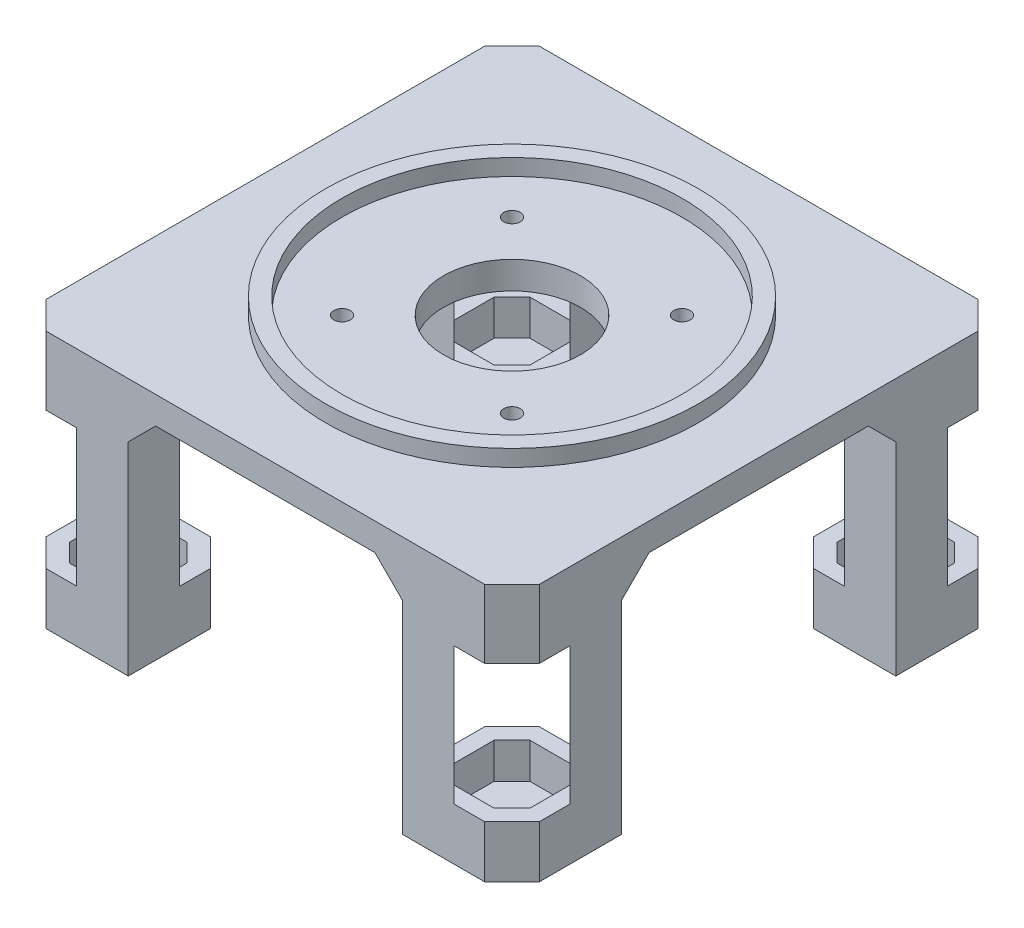
SolidWorks part; units mm, degrees
material "聚脂树脂"
ref_plane "前视基准面" through (0, 0, 0) normal (0, 0, 1) x (1, 0, 0)
ref_plane "上视基准面" through (0, 0, 0) normal (0, 1, 0) x (1, 0, 0)
ref_plane "右视基准面" through (0, 0, 0) normal (1, 0, 0) x (0, 0, -1)
other "Configuration Table"
sketch "草图1" plane through (0, 0, 0) normal (0, 1, 0) x (1, 0, 0)
  line L0 (0, 0) -> (0, 27.7353) construction
  line L1 (-45, -45) -> (45, -45)
  line L2 (-45, -45) -> (-45, 45)
  line L3 (-45, 45) -> (45, 45)
  line L4 (45, -45) -> (45, 45)
  line L5 (-45, -45) -> (45, 45) construction
  line L6 (-45, 45) -> (45, -45) construction
  circle A0 centre (0, 0) radius 12.5
  circle A1 centre (15.5, 15.5) radius 1.5
  circle A2 centre (-15.5, -15.5) radius 1.5
  circle A3 centre (15.5, -15.5) radius 1.5
  circle A4 centre (-15.5, 15.5) radius 1.5
  circle A5 centre (0, 0) radius 34 construction
  point P0 (0, 0)
  dimension "D1" = 25
  dimension "D2" = 3
  dimension "D3" = 31
  dimension "D4" = 31
  dimension "D6" = 68
  dimension "D5" = 90
extrude "凸台-拉伸1" add sketch "草图1" along normal blind 5
chamfer "倒角1" distance 5 angle 45 4 edges at (-45, 2.5, -45) (-45, 2.5, 45) (45, 2.5, -45) (45, 2.5, 45)
sketch "草图2" plane through (0, 5, 0) normal (0, 1, 0) x (1, 0, 0)
  circle A0 centre (0, 0) radius 31
  circle A1 centre (0, 0) radius 34
  dimension "D1" = 62
  dimension "D2" = 68
extrude "凸台-拉伸2" add sketch "草图2" along normal blind 3
sketch "草图3" plane through (0, 0, 0) normal (0, -1, 0) x (1, 0, 0)
  line L0 (0, 0) -> (0, 54.7666) construction
  line L1 (0, 0) -> (54.8608, 0) construction
  line L2 (25, 45) -> (40, 45)
  line L3 (-40, 45) -> (40, 45) construction
  line L4 (40, 45) -> (45, 40)
  line L5 (45, 40) -> (45, 25)
  line L6 (45, 40) -> (45, -40) construction
  line L7 (45, 25) -> (30, 25)
  line L8 (25, 45) -> (25, 30)
  line L9 (25, 30) -> (30, 25)
  line L10 (28, 31.2426) -> (31.2426, 28)
  line L11 (42, 28) -> (31.2426, 28)
  line L12 (42, 38.7574) -> (42, 28)
  line L13 (38.7574, 42) -> (42, 38.7574)
  line L14 (28, 42) -> (38.7574, 42)
  line L15 (28, 42) -> (28, 31.2426)
  line L16 (25, -45) -> (25, -30)
  line L17 (25, -45) -> (40, -45)
  line L18 (40, -45) -> (45, -40)
  line L19 (45, -40) -> (45, -25)
  line L20 (45, -25) -> (30, -25)
  line L21 (25, -30) -> (30, -25)
  line L22 (28, -42) -> (28, -31.2426)
  line L23 (28, -42) -> (38.7574, -42)
  line L24 (38.7574, -42) -> (42, -38.7574)
  line L25 (42, -38.7574) -> (42, -28)
  line L26 (42, -28) -> (31.2426, -28)
  line L27 (28, -31.2426) -> (31.2426, -28)
  line L28 (-25, -45) -> (-40, -45)
  line L29 (-40, -45) -> (-45, -40)
  line L30 (-45, -40) -> (-45, -25)
  line L31 (-45, -25) -> (-30, -25)
  line L32 (-25, -30) -> (-30, -25)
  line L33 (-25, -45) -> (-25, -30)
  line L34 (-28, -42) -> (-38.7574, -42)
  line L35 (-38.7574, -42) -> (-42, -38.7574)
  line L36 (-42, -38.7574) -> (-42, -28)
  line L37 (-42, -28) -> (-31.2426, -28)
  line L38 (-28, -31.2426) -> (-31.2426, -28)
  line L39 (-28, -42) -> (-28, -31.2426)
  line L40 (-25, 45) -> (-25, 30)
  line L41 (-25, 45) -> (-40, 45)
  line L42 (-40, 45) -> (-45, 40)
  line L43 (-45, 40) -> (-45, 25)
  line L44 (-45, 25) -> (-30, 25)
  line L45 (-25, 30) -> (-30, 25)
  line L46 (-28, 42) -> (-28, 31.2426)
  line L47 (-28, 42) -> (-38.7574, 42)
  line L48 (-38.7574, 42) -> (-42, 38.7574)
  line L49 (-42, 38.7574) -> (-42, 28)
  line L50 (-42, 28) -> (-31.2426, 28)
  line L51 (-28, 31.2426) -> (-31.2426, 28)
  circle A0 centre (0, 0) radius 30 construction
  dimension "D2" = 60
  dimension "D3" = 5
  dimension "D1" = 15
  dimension "D4" = 5
  dimension "D5" = 15
  dimension "D6" = 3
extrude "凸台-拉伸3" add sketch "草图3" along normal blind 42
chamfer "倒角2" distance 5 angle 45 8 edges at (37.5, 0, -25) (25, 0, 37.5) (37.5, 0, 25) (25, 0, -37.5) (-25, 0, 37.5) (-37.5, 0, 25) (-25, 0, -37.5) (-37.5, 0, -25)
sketch "草图4" plane through (-42.5, 0, 42.5) normal (-0.7071, 0, 0.7071) x (0.7071, 0, 0.7071)
  line L0 (0, 0) -> (0, -44.657) construction
  line L1 (-3.5355, 5) -> (3.5355, 5) construction
  line L2 (-7.5, -32.5) -> (7.5, -32.5)
  line L3 (-7.5, -32.5) -> (-7.5, -7.5)
  line L4 (-7.5, -7.5) -> (7.5, -7.5)
  line L5 (7.5, -32.5) -> (7.5, -7.5)
  line L6 (-7.5, -32.5) -> (7.5, -7.5) construction
  line L7 (-7.5, -7.5) -> (7.5, -32.5) construction
  point P3 (0, -20)
  dimension "D1" = 15
  dimension "D2" = 25
  dimension "D3" = 25
extrude "切除-拉伸1" cut sketch "草图4" against normal blind 157
pattern_circular "阵列(圆周)1" count 2 over 90 about axis through (0, 8, 0) along (0, -1, 0) of "切除-拉伸1"
sketch "草图5" plane through (0, -42, 0) normal (0, -1, 0) x (1, 0, 0)
  line L0 (-25, -45) -> (-25, -30) construction
  line L1 (-25, -30) -> (-30, -25) construction
  line L2 (-30, -25) -> (-45, -25) construction
  line L3 (-45, -25) -> (-45, -40) construction
  line L4 (-45, -40) -> (-40, -45) construction
  line L5 (-40, -45) -> (-25, -45) construction
  line L6 (40, -45) -> (45, -40) construction
  line L7 (45, -40) -> (45, -25) construction
  line L8 (45, -25) -> (30, -25) construction
  line L9 (30, -25) -> (25, -30) construction
  line L10 (25, -30) -> (25, -45) construction
  line L11 (25, -45) -> (40, -45) construction
  line L12 (25, 45) -> (25, 30) construction
  line L13 (25, 30) -> (30, 25) construction
  line L14 (30, 25) -> (45, 25) construction
  line L15 (45, 25) -> (45, 40) construction
  line L16 (45, 40) -> (40, 45) construction
  line L17 (40, 45) -> (25, 45) construction
  line L18 (-40, 45) -> (-45, 40) construction
  line L19 (-45, 40) -> (-45, 25) construction
  line L20 (-45, 25) -> (-30, 25) construction
  line L21 (-30, 25) -> (-25, 30) construction
  line L22 (-25, 30) -> (-25, 45) construction
  line L23 (-25, 45) -> (-40, 45) construction
  line L24 (-25, -45) -> (-25, -30)
  line L25 (-25, -30) -> (-30, -25)
  line L26 (-30, -25) -> (-45, -25)
  line L27 (-45, -25) -> (-45, -40)
  line L28 (-45, -40) -> (-40, -45)
  line L29 (-40, -45) -> (-25, -45)
  line L30 (40, -45) -> (45, -40)
  line L31 (45, -40) -> (45, -25)
  line L32 (45, -25) -> (30, -25)
  line L33 (30, -25) -> (25, -30)
  line L34 (25, -30) -> (25, -45)
  line L35 (25, -45) -> (40, -45)
  line L36 (25, 45) -> (25, 30)
  line L37 (25, 30) -> (30, 25)
  line L38 (30, 25) -> (45, 25)
  line L39 (45, 25) -> (45, 40)
  line L40 (45, 40) -> (40, 45)
  line L41 (40, 45) -> (25, 45)
  line L42 (-40, 45) -> (-45, 40)
  line L43 (-45, 40) -> (-45, 25)
  line L44 (-45, 25) -> (-30, 25)
  line L45 (-30, 25) -> (-25, 30)
  line L46 (-25, 30) -> (-25, 45)
  line L47 (-25, 45) -> (-40, 45)
  line L48 (0, 0) -> (0, 47.372) construction
  line L49 (0, 0) -> (72.5778, 0) construction
  circle A0 centre (-35, 35) radius 1.5
  circle A1 centre (35, 35) radius 1.5
  circle A2 centre (35, -35) radius 1.5
  circle A3 centre (-35, -35) radius 1.5
  dimension "D1" = 3
  dimension "D2" = 10
  dimension "D3" = 10
extrude "凸台-拉伸4" add sketch "草图5" against normal blind 3
